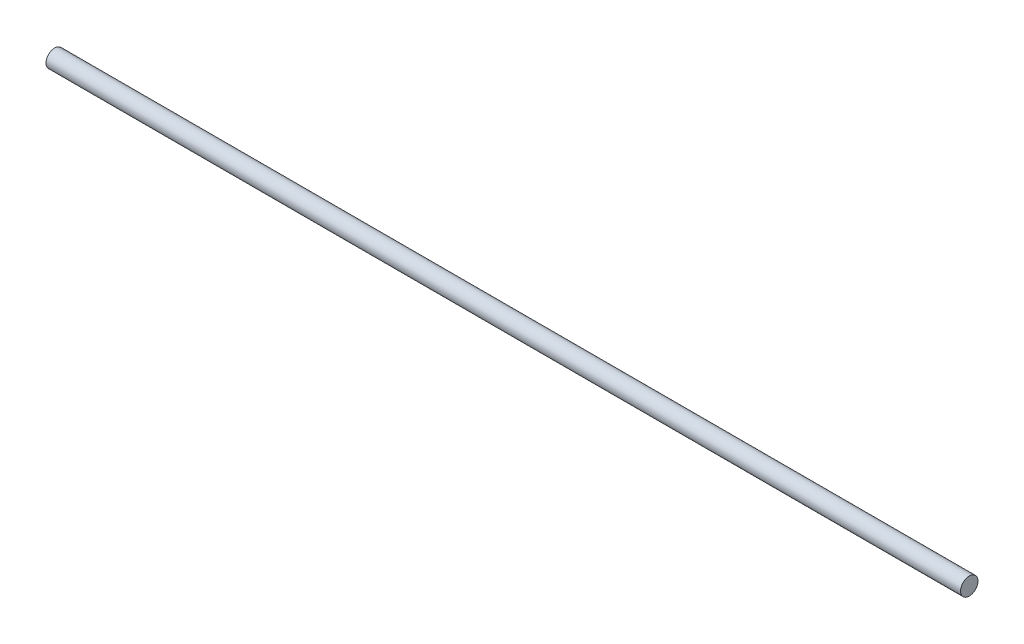
SolidWorks part; units mm, degrees
material "Alloy Steel"
ref_plane "Front Plane" through (0, 0, 0) normal (0, 0, 1) x (1, 0, 0)
ref_plane "Top Plane" through (0, 0, 0) normal (0, 1, 0) x (1, 0, 0)
ref_plane "Right Plane" through (0, 0, 0) normal (1, 0, 0) x (0, 0, -1)
sketch "Sketch1" plane through (0, 0, 0) normal (1, 0, 0) x (0, 0, -1)
  circle A0 centre (0, 0) radius 4
  dimension "D1" = 8
extrude "Boss-Extrude1" add sketch "Sketch1" along normal blind 420
